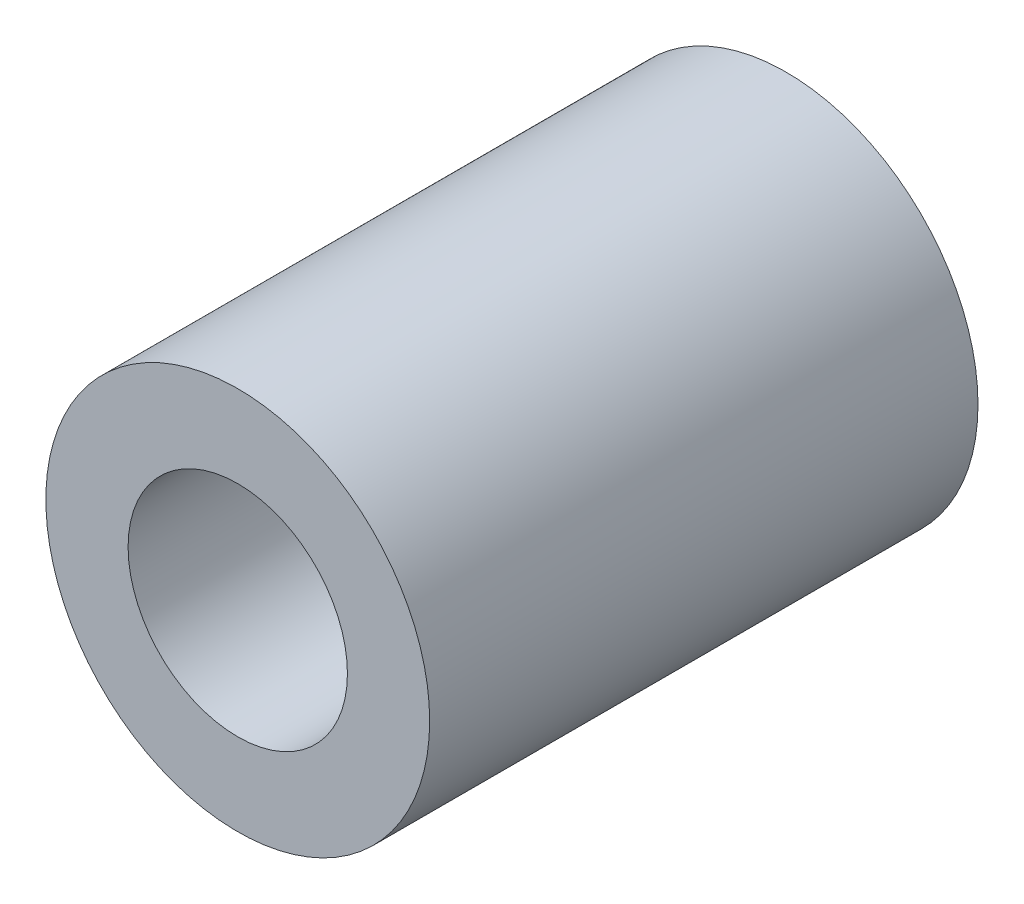
SolidWorks part; units mm, degrees
ref_plane "Front Plane" through (0, 0, 0) normal (0, 0, 1) x (1, 0, 0)
ref_plane "Top Plane" through (0, 0, 0) normal (0, 1, 0) x (1, 0, 0)
ref_plane "Right Plane" through (0, 0, 0) normal (1, 0, 0) x (0, 0, -1)
sketch "Sketch2" plane through (0, 0, 0) normal (0, 0, 1) x (1, 0, 0)
  circle A0 centre (0, 0) radius 6
  circle A1 centre (0, 0) radius 10.5
extrude "Boss-Extrude1" add sketch "Sketch2" along normal blind 30
